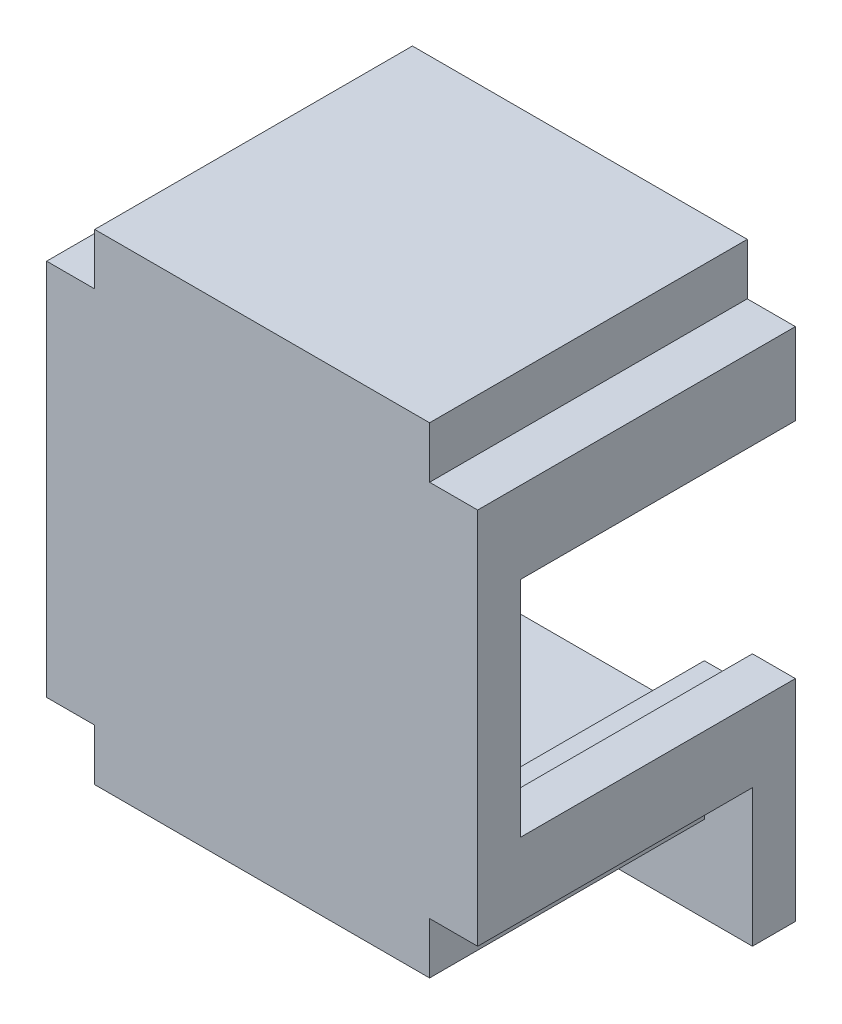
SolidWorks part; units mm, degrees
ref_plane "Front Plane" through (0, 0, 0) normal (0, 0, 1) x (1, 0, 0)
ref_plane "Top Plane" through (0, 0, 0) normal (0, 1, 0) x (1, 0, 0)
ref_plane "Right Plane" through (0, 0, 0) normal (1, 0, 0) x (0, 0, -1)
sketch "Sketch1" plane through (0, 0, 0) normal (0, 0, 1) x (-1, 0, 0)
  line L0 (-29.8461, 76.2659) -> (-29.8461, 79.7659)
  line L1 (-29.8461, 79.7659) -> (-24.2461, 79.7659)
  line L2 (-24.2461, 79.7659) -> (-24.2461, 85.7659)
  line L4 (-24.2461, 85.7659) -> (4.7539, 85.7659)
  line L6 (4.7539, 85.7659) -> (4.7539, 79.7659)
  line L7 (4.7539, 79.7659) -> (10.3539, 79.7659)
  line L8 (10.3539, 79.7659) -> (10.3539, 76.2659)
  line L9 (-29.8461, 50.2659) -> (-29.8461, 45.7659)
  line L10 (-34.8461, 76.2659) -> (-34.8461, 84.7659)
  line L11 (-34.8461, 84.7659) -> (-29.2461, 84.7659)
  line L12 (-29.2461, 84.7659) -> (-29.2461, 90.7659)
  line L13 (-29.2461, 90.7659) -> (9.7539, 90.7659)
  line L14 (9.7539, 90.7659) -> (9.7539, 84.7659)
  line L15 (9.7539, 84.7659) -> (15.3539, 84.7659)
  line L16 (15.3539, 84.7659) -> (15.3539, 76.2659)
  line L17 (10.3539, 76.2659) -> (15.3539, 76.2659)
  line L18 (-34.8461, 76.2659) -> (-29.8461, 76.2659)
  line L19 (-29.8461, 45.7659) -> (-24.2461, 45.7659)
  line L20 (-24.2461, 45.7659) -> (-24.2461, 39.7659)
  line L22 (-24.2461, 39.7659) -> (4.7539, 39.7659)
  line L24 (4.7539, 39.7659) -> (4.7539, 45.7659)
  line L26 (4.7539, 45.7659) -> (10.3539, 45.7659)
  line L27 (10.3539, 45.7659) -> (10.3539, 50.2659)
  line L28 (-34.8461, 50.2659) -> (-34.8461, 40.7659)
  line L29 (-34.8461, 40.7659) -> (-29.2461, 40.7659)
  line L30 (-29.2461, 40.7659) -> (-29.2461, 34.7659)
  line L31 (-29.2461, 34.7659) -> (9.7539, 34.7659)
  line L32 (9.7539, 34.7659) -> (9.7539, 40.7659)
  line L33 (9.7539, 40.7659) -> (15.3539, 40.7659)
  line L34 (15.3539, 40.7659) -> (15.3539, 50.2659)
  line L35 (-29.8461, 50.2659) -> (-34.8461, 50.2659)
  line L36 (10.3539, 50.2659) -> (15.3539, 50.2659)
  point P8 (0, 0)
  point P9 (0, 0)
  point P11 (0, 0)
  dimension "D1" = 6
  dimension "D2" = 5
  dimension "D3" = 5
extrude "Boss-Extrude1" add sketch "Sketch1" along normal blind 32 contours L22 L24 L26 L27 L36 L34 L33 L32 L31 L30 L29 L28 L35 L9 L19 L20 | L6 L7 L8 L17 L16 L15 L14 L13 L12 L11 L10 L18 L0 L1 L2 L4
sketch "Sketch2" plane through (0, 0, 32) normal (0, 0, 1) x (1, 0, 0)
  line L0 (-9.7539, -34.7659) -> (-9.7539, -40.7659)
  line L1 (-9.7539, -40.7659) -> (-15.3539, -40.7659)
  line L2 (-15.3539, -40.7659) -> (-15.3539, -84.7659)
  line L3 (-15.3539, -84.7659) -> (-9.7539, -84.7659)
  line L4 (-9.7539, -84.7659) -> (-9.7539, -90.7659)
  line L5 (-9.7539, -90.7659) -> (29.2461, -90.7659)
  line L6 (29.2461, -90.7659) -> (29.2461, -84.7659)
  line L7 (29.2461, -84.7659) -> (34.8461, -84.7659)
  line L8 (34.8461, -84.7659) -> (34.8461, -40.7659)
  line L9 (34.8461, -40.7659) -> (29.2461, -40.7659)
  line L10 (29.2461, -40.7659) -> (29.2461, -34.7659)
  line L11 (29.2461, -34.7659) -> (-9.7539, -34.7659)
extrude "Boss-Extrude2" add sketch "Sketch2" along normal blind 5
sketch "Sketch4" plane through (0, 0, 0) normal (0, 0, -1) x (-1, 0, 0)
  line L0 (-29.2461, -90.7659) -> (9.7539, -90.7659) construction
  line L2 (-34.8461, -84.7659) -> (-34.8461, -100.7659)
  line L3 (-34.8461, -100.7659) -> (15.3539, -100.7659)
  line L4 (15.3539, -84.7659) -> (15.3539, -100.7659)
  line L5 (15.3539, -84.7659) -> (15.3539, -76.2659) construction
  line L6 (-34.8461, -84.7659) -> (-29.2461, -84.7659)
  line L7 (-29.2461, -84.7659) -> (-29.2461, -90.7659)
  line L8 (-29.2461, -90.7659) -> (9.7539, -90.7659)
  line L9 (9.7539, -90.7659) -> (9.7539, -84.7659)
  line L10 (9.7539, -84.7659) -> (15.3539, -84.7659)
  dimension "D1" = 10
extrude "Boss-Extrude3" add sketch "Sketch4" against normal blind 5
